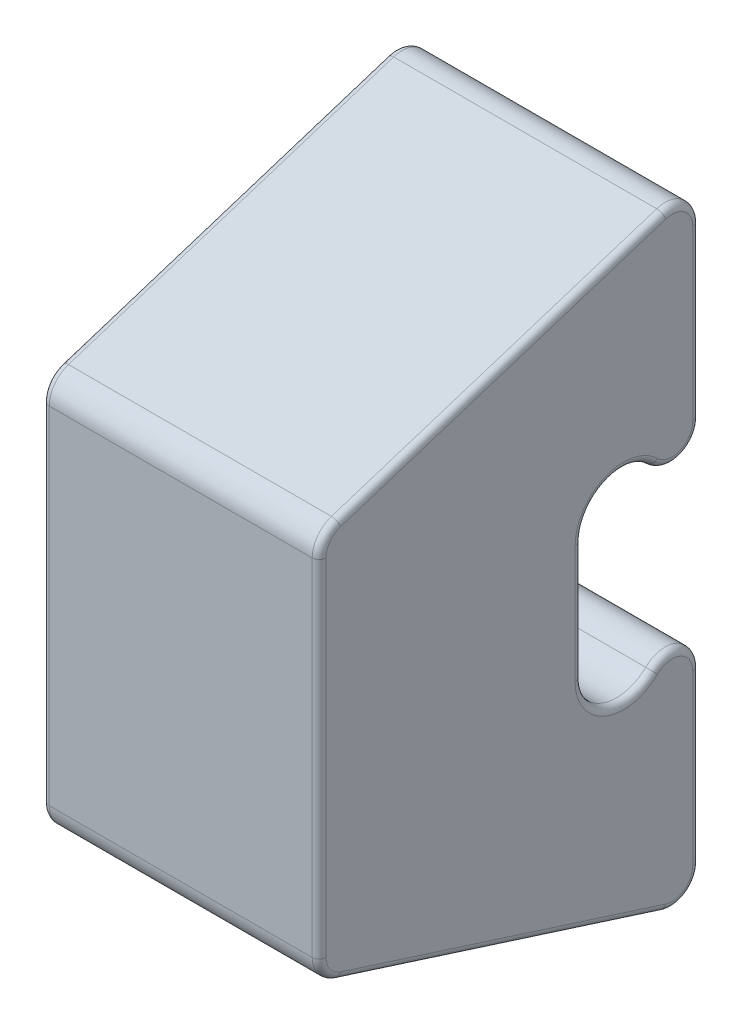
SolidWorks part; units mm, degrees
material "ABS"
ref_plane "Front Plane" through (0, 0, 0) normal (1, 0, 0) x (0, 1, 0)
ref_plane "Top Plane" through (0, 0, 0) normal (0, 0, 1) x (0, 1, 0)
ref_plane "Right Plane" through (0, 0, 0) normal (0, 1, 0) x (-1, 0, 0)
sketch "Sketch3" plane through (0, 0, 0) normal (1, 0, 0) x (0, 1, 0)
  line L12 (-4, 5.4) -> (-1.5642, 5.4)
  line L13 (-0.85, 7.1) -> (0.85, 7.1)
  line L14 (1.5642, 5.4) -> (4, 5.4)
  line L15 (4.3811, 5.9216) -> (2.8811, 10.6216)
  line L16 (2.5, 10.9) -> (-2.5, 10.9)
  line L17 (-2.8811, 10.6216) -> (-4.3811, 5.9216)
  line L18 (-4, 5.4) -> (-1.5642, 5.4)
  line L19 (-0.85, 7.1) -> (0.85, 7.1)
  line L20 (1.5642, 5.4) -> (4, 5.4)
  line L21 (4.3811, 5.9216) -> (2.8811, 10.6216)
  line L22 (2.5, 10.9) -> (-2.5, 10.9)
  line L23 (-2.8811, 10.6216) -> (-4.3811, 5.9216)
  arc A16 (-4.3811, 5.9216) -> (-4, 5.4) centre (-4, 5.8) ccw
  arc A17 (-1.5642, 5.4) -> (-1.2785, 6.08) centre (-1.5642, 5.8) ccw
  arc A18 (-0.85, 7.1) -> (-1.2785, 6.08) centre (-0.85, 6.5) ccw
  arc A19 (1.2785, 6.08) -> (0.85, 7.1) centre (0.85, 6.5) ccw
  arc A20 (1.2785, 6.08) -> (1.5642, 5.4) centre (1.5642, 5.8) ccw
  arc A21 (4, 5.4) -> (4.3811, 5.9216) centre (4, 5.8) ccw
  arc A22 (2.8811, 10.6216) -> (2.5, 10.9) centre (2.5, 10.5) ccw
  arc A23 (-2.5, 10.9) -> (-2.8811, 10.6216) centre (-2.5, 10.5) ccw
  arc A24 (-4.3811, 5.9216) -> (-4, 5.4) centre (-4, 5.8) ccw
  arc A25 (-1.5642, 5.4) -> (-1.2785, 6.08) centre (-1.5642, 5.8) ccw
  arc A26 (-0.85, 7.1) -> (-1.2785, 6.08) centre (-0.85, 6.5) ccw
  arc A27 (1.2785, 6.08) -> (0.85, 7.1) centre (0.85, 6.5) ccw
  arc A28 (1.2785, 6.08) -> (1.5642, 5.4) centre (1.5642, 5.8) ccw
  arc A29 (4, 5.4) -> (4.3811, 5.9216) centre (4, 5.8) ccw
  arc A30 (2.8811, 10.6216) -> (2.5, 10.9) centre (2.5, 10.5) ccw
  arc A31 (-2.5, 10.9) -> (-2.8811, 10.6216) centre (-2.5, 10.5) ccw
  dimension "D1" = 0.01
extrude "Boss-Extrude1" add sketch "Sketch3" along normal blind 1 and the other way blind 3
fillet "Fillet1" radius 0.1 28 edges at (-3, -2.7821, 5.4) (-3, -1.1954, 5.6451) (-3, -1.4032, 6.7324) (-3, 0, 7.1) (-3, 1.4032, 6.7324) (-3, 1.1954, 5.6451) (-3, 2.7821, 5.4) (-3, 4.323, 5.564) (-3, 3.6311, 8.2716) (-3, 2.736, 10.823) (-3, 0, 10.9) (-3, -2.736, 10.823) (-3, -3.6311, 8.2716) (-3, -4.323, 5.564) (1, -3.6311, 8.2716) (1, -2.736, 10.823) (1, 0, 10.9) (1, 2.736, 10.823) (1, 3.6311, 8.2716) (1, 4.323, 5.564) (1, 2.7821, 5.4) (1, 1.1954, 5.6451) (1, 1.4032, 6.7324) (1, 0, 7.1) (1, -1.4032, 6.7324) (1, -1.1954, 5.6451) (1, -2.7821, 5.4) (1, -4.323, 5.564)
